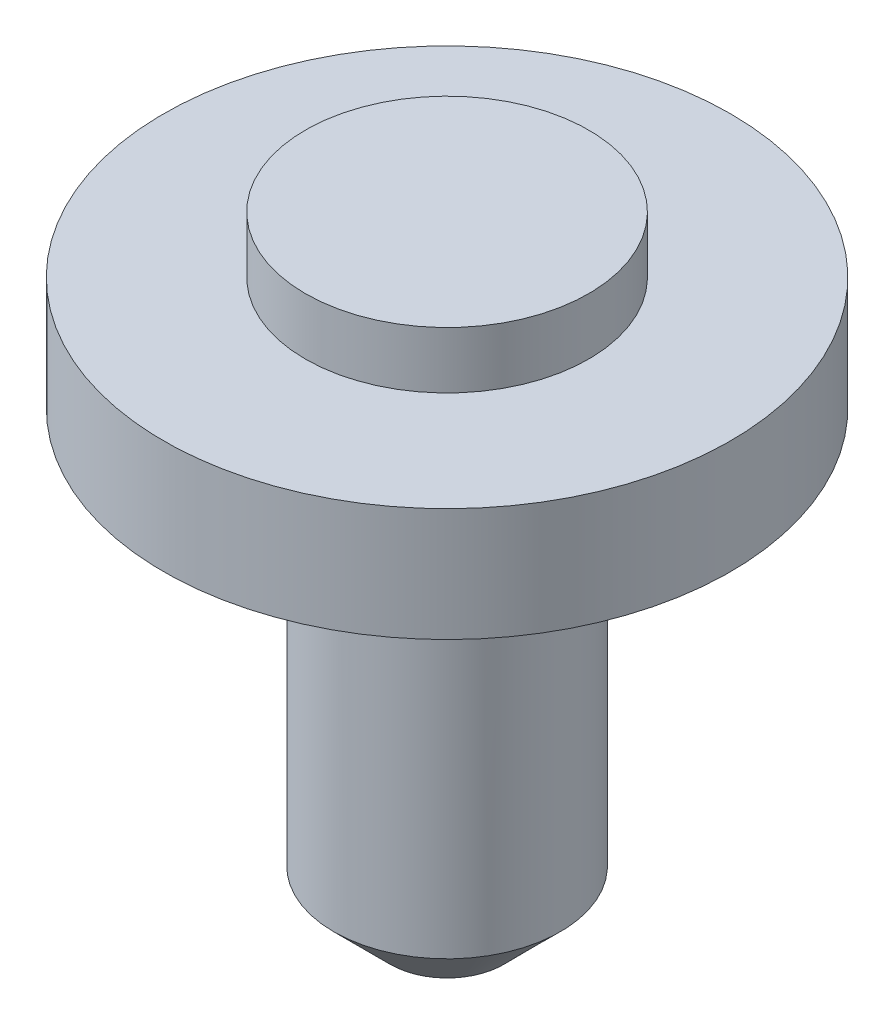
SolidWorks part; units mm, degrees
ref_plane "Front Plane" through (0, 0, 0) normal (0, 0, 1) x (1, 0, 0)
ref_plane "Top Plane" through (0, 0, 0) normal (0, 1, 0) x (1, 0, 0)
ref_plane "Right Plane" through (0, 0, 0) normal (1, 0, 0) x (0, 0, -1)
sketch "Sketch1" plane through (0, 0, 0) normal (0, 0, 1) x (1, 0, 0)
  line L0 (0, 0) -> (0, 9.0055) construction
  line L1 (0, 10) -> (-5, 10)
  line L2 (-5, 10) -> (-5, 8)
  line L3 (-5, 8) -> (-2.5, 8)
  line L4 (-2.5, 8) -> (-2.5, 7)
  line L5 (-2.5, 7) -> (-2, 7)
  line L6 (-2, 7) -> (-2, 0)
  line L7 (-2, 0) -> (-0.35, 0)
  line L8 (-0.35, 0) -> (-0.35, 9)
  line L9 (-0.35, 9) -> (0, 9)
  line L10 (0, 10) -> (0, 9)
  dimension "D1" = 10
  dimension "D2" = 2
  dimension "D3" = 5
  dimension "D4" = 1
  dimension "D5" = 10
  dimension "D6" = 4
  dimension "D7" = 0.7
  dimension "D8" = 9
revolve "Revolve1" add sketch "Sketch1" angle 360 about L0
chamfer "Chamfer1" distance 1 angle 45 1 edges at (0, 0, -2)
sketch "Sketch2" plane through (0, 10, 0) normal (0, 1, 0) x (1, 0, 0)
  circle A0 centre (0, 0) radius 2.5 construction
  circle A1 centre (0, 0) radius 2.5
extrude "Boss-Extrude1" add sketch "Sketch2" along normal blind 1
